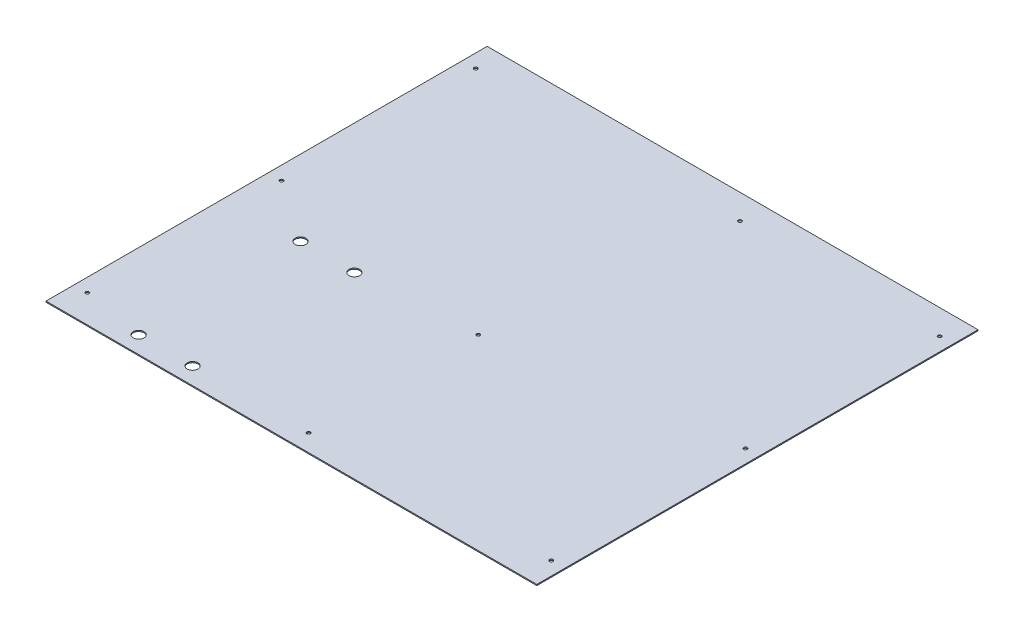
SolidWorks part; units mm, degrees
material "acero"
ref_plane "Alzado" through (0, 0, 0) normal (0, 0, 1) x (1, 0, 0)
ref_plane "Planta" through (0, 0, 0) normal (0, 1, 0) x (1, 0, 0)
ref_plane "Vista lateral" through (0, 0, 0) normal (1, 0, 0) x (0, 0, -1)
sketch "Croquis1" plane through (0, 0, 0) normal (0, 1, 0) x (1, 0, 0)
  line L1 (-227.5, -204.5) -> (227.5, -204.5)
  line L2 (-227.5, -204.5) -> (-227.5, 204.5)
  line L3 (-227.5, 204.5) -> (227.5, 204.5)
  line L4 (227.5, -204.5) -> (227.5, 204.5)
  line L5 (-227.5, -204.5) -> (227.5, 204.5) construction
  line L6 (-227.5, 204.5) -> (227.5, -204.5) construction
  point P0 (0, 0)
  dimension "D1" = 455
  dimension "D2" = 409
extrude "Saliente-Extruir1" add sketch "Croquis1" along normal blind 1
sketch "Croquis2" plane through (0, 0, 0) normal (0, -1, 0) x (1, 0, 0)
  line L0 (-227.5, 204.5) -> (227.5, 204.5) construction
  line L1 (227.5, 204.5) -> (227.5, -204.5) construction
  line L2 (0, 0) -> (0, -204.5) construction
  line L3 (227.5, -204.5) -> (-227.5, -204.5) construction
  circle A0 centre (-215, 178.6) radius 1.6
  circle A1 centre (-215, -181.4) radius 1.6
  circle A2 centre (215, -181.4) radius 1.6
  circle A3 centre (215, 178.6) radius 1.6
  circle A4 centre (0, 31.25) radius 1.6
  dimension "D1" = 3.2
  dimension "D2" = 173.25
  dimension "D5" = 360
  dimension "D3" = 227.5
  dimension "D4" = 430
  dimension "D7" = 25.9
extrude "Cortar-Extruir1" cut sketch "Croquis2" against normal up to next
sketch "Croquis3" plane through (0, 0, 0) normal (0, -1, 0) x (1, 0, 0)
  line L0 (-227.5, 204.5) -> (227.5, 204.5) construction
  line L1 (-227.5, -204.5) -> (-227.5, 204.5) construction
  circle A0 centre (-157.5, 38.6) radius 5
  circle A1 centre (-107.5, 38.6) radius 5
  circle A2 centre (-107.5, 188.6) radius 5
  circle A3 centre (-157.5, 188.6) radius 5
  dimension "D1" = 10
  dimension "D3" = 50
  dimension "D6" = 70
  dimension "D2" = 50
  dimension "D4" = 150
  dimension "D5" = 15.9
extrude "Cortar-Extruir2" cut sketch "Croquis3" against normal up to next
sketch "Croquis4" plane through (0, 0, 0) normal (0, -1, 0) x (1, 0, 0)
  line L0 (-215, -181.4) -> (215, -181.4) construction
  line L1 (215, -181.4) -> (215, 178.6) construction
  line L2 (215, 178.6) -> (-215, 178.6) construction
  line L3 (-215, 178.6) -> (-215, -181.4) construction
  circle A0 centre (-215, -1.4) radius 1.6
  circle A1 centre (215, -1.4) radius 1.6
  circle A2 centre (0, 188.6) radius 1.6
  circle A3 centre (30, -181.4) radius 1.6
  circle A4 centre (0, 31.25) radius 1.6 construction
  point P12 (0, -181.4)
  point P13 (0, 178.6)
  dimension "D1" = 30
  dimension "D2" = 10
extrude "Cortar-Extruir3" cut sketch "Croquis4" against normal up to next
